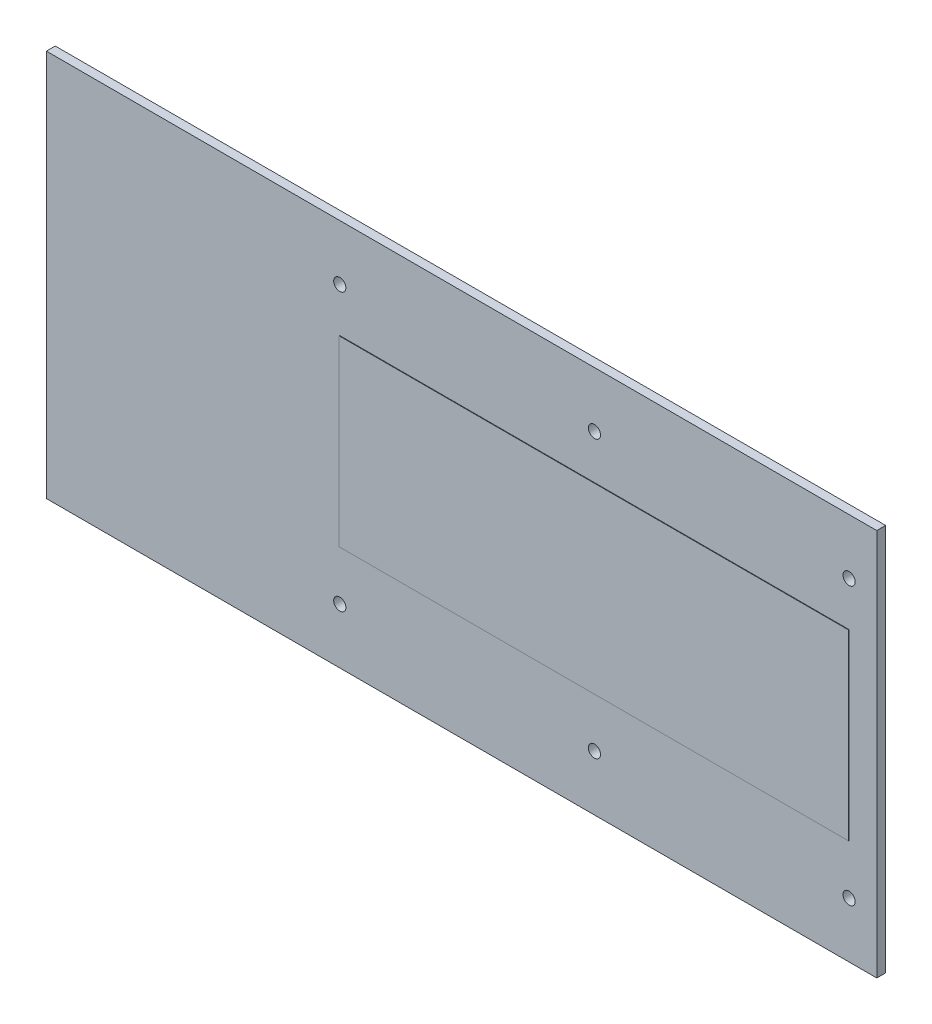
SolidWorks part; units mm, degrees
ref_plane "Front Plane" through (0, 0, 0) normal (0, 0, 1) x (1, 0, 0)
ref_plane "Top Plane" through (0, 0, 0) normal (0, 1, 0) x (1, 0, 0)
ref_plane "Right Plane" through (0, 0, 0) normal (1, 0, 0) x (0, 0, -1)
curve "ImportedCurve1"
curve "ImportedCurve2"
curve "ImportedCurve3"
curve "ImportedCurve4"
curve "ImportedCurve5"
curve "ImportedCurve6"
curve "ImportedCurve7"
curve "ImportedCurve8"
curve "ImportedCurve9"
curve "ImportedCurve10"
curve "ImportedCurve11"
curve "ImportedCurve12"
curve "ImportedCurve13"
curve "ImportedCurve14"
curve "ImportedCurve15"
curve "ImportedCurve16"
curve "ImportedCurve17"
curve "ImportedCurve18"
curve "ImportedCurve19"
curve "ImportedCurve20"
curve "ImportedCurve21"
curve "ImportedCurve22"
curve "ImportedCurve23"
curve "ImportedCurve24"
curve "ImportedCurve25"
curve "ImportedCurve26"
curve "ImportedCurve27"
curve "ImportedCurve28"
curve "ImportedCurve29"
curve "ImportedCurve30"
curve "ImportedCurve31"
curve "ImportedCurve32"
curve "ImportedCurve33"
curve "ImportedCurve34"
curve "ImportedCurve35"
curve "ImportedCurve36"
curve "ImportedCurve37"
curve "ImportedCurve38"
curve "ImportedCurve39"
curve "ImportedCurve40"
curve "ImportedCurve41"
curve "ImportedCurve42"
curve "ImportedCurve43"
curve "ImportedCurve44"
curve "ImportedCurve45"
curve "ImportedCurve46"
curve "ImportedCurve47"
curve "ImportedCurve48"
curve "ImportedCurve49"
curve "ImportedCurve50"
curve "ImportedCurve51"
curve "ImportedCurve52"
curve "ImportedCurve53"
curve "ImportedCurve54"
curve "ImportedCurve55"
curve "ImportedCurve56"
curve "ImportedCurve57"
curve "ImportedCurve58"
curve "ImportedCurve59"
curve "ImportedCurve60"
curve "ImportedCurve61"
curve "ImportedCurve62"
curve "ImportedCurve63"
curve "ImportedCurve64"
curve "ImportedCurve65"
curve "ImportedCurve66"
curve "ImportedCurve67"
curve "ImportedCurve68"
curve "ImportedCurve69"
curve "ImportedCurve70"
curve "ImportedCurve71"
curve "ImportedCurve72"
curve "ImportedCurve73"
curve "ImportedCurve74"
curve "ImportedCurve75"
curve "ImportedCurve76"
curve "ImportedCurve77"
curve "ImportedCurve78"
curve "ImportedCurve79"
curve "ImportedCurve80"
curve "ImportedCurve81"
curve "ImportedCurve82"
curve "ImportedCurve83"
curve "ImportedCurve84"
curve "ImportedCurve85"
curve "ImportedCurve86"
curve "ImportedCurve87"
curve "ImportedCurve88"
curve "ImportedCurve89"
curve "ImportedCurve90"
curve "ImportedCurve91"
curve "ImportedCurve92"
curve "ImportedCurve93"
curve "ImportedCurve94"
curve "ImportedCurve95"
curve "ImportedCurve96"
curve "ImportedCurve97"
curve "ImportedCurve98"
curve "ImportedCurve99"
curve "ImportedCurve100"
curve "ImportedCurve101"
curve "ImportedCurve102"
curve "ImportedCurve103"
curve "ImportedCurve104"
curve "ImportedCurve105"
curve "ImportedCurve106"
curve "ImportedCurve107"
curve "ImportedCurve108"
curve "ImportedCurve109"
curve "ImportedCurve110"
curve "ImportedCurve111"
curve "ImportedCurve112"
curve "ImportedCurve113"
curve "ImportedCurve114"
curve "ImportedCurve115"
curve "ImportedCurve116"
curve "ImportedCurve117"
curve "ImportedCurve118"
curve "ImportedCurve119"
curve "ImportedCurve120"
curve "ImportedCurve121"
curve "ImportedCurve122"
curve "ImportedCurve123"
curve "ImportedCurve124"
curve "ImportedCurve125"
curve "ImportedCurve126"
curve "ImportedCurve127"
curve "ImportedCurve128"
curve "ImportedCurve129"
curve "ImportedCurve130"
curve "ImportedCurve131"
curve "ImportedCurve132"
curve "ImportedCurve133"
curve "ImportedCurve134"
curve "ImportedCurve135"
curve "ImportedCurve136"
curve "ImportedCurve137"
curve "ImportedCurve138"
curve "ImportedCurve139"
curve "ImportedCurve140"
curve "ImportedCurve141"
curve "ImportedCurve142"
curve "ImportedCurve143"
curve "ImportedCurve144"
curve "ImportedCurve145"
curve "ImportedCurve146"
curve "ImportedCurve147"
curve "ImportedCurve148"
curve "ImportedCurve149"
curve "ImportedCurve150"
curve "ImportedCurve151"
curve "ImportedCurve152"
curve "ImportedCurve153"
curve "ImportedCurve154"
curve "ImportedCurve155"
curve "ImportedCurve156"
curve "ImportedCurve157"
curve "ImportedCurve158"
curve "ImportedCurve159"
curve "ImportedCurve160"
curve "ImportedCurve161"
curve "ImportedCurve162"
curve "ImportedCurve163"
curve "ImportedCurve164"
curve "ImportedCurve165"
curve "ImportedCurve166"
curve "ImportedCurve167"
curve "ImportedCurve168"
curve "ImportedCurve169"
curve "ImportedCurve170"
curve "ImportedCurve171"
curve "ImportedCurve172"
curve "ImportedCurve173"
curve "ImportedCurve174"
curve "ImportedCurve175"
curve "ImportedCurve176"
curve "ImportedCurve177"
curve "ImportedCurve178"
curve "ImportedCurve179"
curve "ImportedCurve180"
curve "ImportedCurve181"
curve "ImportedCurve182"
curve "ImportedCurve183"
curve "ImportedCurve184"
curve "ImportedCurve185"
curve "ImportedCurve186"
curve "ImportedCurve187"
curve "ImportedCurve188"
curve "ImportedCurve189"
curve "ImportedCurve190"
curve "ImportedCurve191"
curve "ImportedCurve192"
curve "ImportedCurve193"
curve "ImportedCurve194"
curve "ImportedCurve195"
curve "ImportedCurve196"
curve "ImportedCurve197"
curve "ImportedCurve198"
curve "ImportedCurve199"
curve "ImportedCurve200"
curve "ImportedCurve201"
curve "ImportedCurve202"
curve "ImportedCurve203"
curve "ImportedCurve204"
curve "ImportedCurve205"
curve "ImportedCurve206"
curve "ImportedCurve207"
curve "ImportedCurve208"
curve "ImportedCurve209"
curve "ImportedCurve210"
curve "ImportedCurve211"
curve "ImportedCurve212"
curve "ImportedCurve213"
curve "ImportedCurve214"
curve "ImportedCurve215"
curve "ImportedCurve216"
curve "ImportedCurve217"
curve "ImportedCurve218"
curve "ImportedCurve219"
curve "ImportedCurve220"
curve "ImportedCurve221"
curve "ImportedCurve222"
curve "ImportedCurve223"
curve "ImportedCurve224"
curve "ImportedCurve225"
curve "ImportedCurve226"
curve "ImportedCurve227"
curve "ImportedCurve228"
curve "ImportedCurve229"
curve "ImportedCurve230"
curve "ImportedCurve231"
curve "ImportedCurve232"
curve "ImportedCurve233"
curve "ImportedCurve234"
curve "ImportedCurve235"
curve "ImportedCurve236"
curve "ImportedCurve237"
curve "ImportedCurve238"
curve "ImportedCurve239"
curve "ImportedCurve240"
curve "ImportedCurve241"
curve "ImportedCurve242"
curve "ImportedCurve243"
curve "ImportedCurve244"
curve "ImportedCurve245"
curve "ImportedCurve246"
curve "ImportedCurve247"
curve "ImportedCurve248"
curve "ImportedCurve249"
curve "ImportedCurve250"
curve "ImportedCurve251"
curve "ImportedCurve252"
curve "ImportedCurve253"
curve "ImportedCurve254"
curve "ImportedCurve255"
curve "ImportedCurve256"
curve "ImportedCurve257"
curve "ImportedCurve258"
curve "ImportedCurve259"
curve "ImportedCurve260"
curve "ImportedCurve261"
curve "ImportedCurve262"
curve "ImportedCurve263"
curve "ImportedCurve264"
curve "ImportedCurve265"
curve "ImportedCurve266"
curve "ImportedCurve267"
curve "ImportedCurve268"
curve "ImportedCurve269"
curve "ImportedCurve270"
curve "ImportedCurve271"
curve "ImportedCurve272"
curve "ImportedCurve273"
curve "ImportedCurve274"
curve "ImportedCurve275"
curve "ImportedCurve276"
curve "ImportedCurve277"
curve "ImportedCurve278"
curve "ImportedCurve279"
curve "ImportedCurve280"
curve "ImportedCurve281"
curve "ImportedCurve282"
curve "ImportedCurve283"
curve "ImportedCurve284"
curve "ImportedCurve285"
curve "ImportedCurve286"
curve "ImportedCurve287"
curve "ImportedCurve288"
curve "ImportedCurve289"
curve "ImportedCurve290"
curve "ImportedCurve291"
curve "ImportedCurve292"
curve "ImportedCurve293"
curve "ImportedCurve294"
curve "ImportedCurve295"
curve "ImportedCurve296"
curve "ImportedCurve297"
curve "ImportedCurve298"
curve "ImportedCurve299"
curve "ImportedCurve300"
curve "ImportedCurve301"
curve "ImportedCurve302"
curve "ImportedCurve303"
curve "ImportedCurve304"
curve "ImportedCurve305"
curve "ImportedCurve306"
curve "ImportedCurve307"
curve "ImportedCurve308"
curve "ImportedCurve309"
curve "ImportedCurve310"
curve "ImportedCurve311"
curve "ImportedCurve312"
curve "ImportedCurve313"
curve "ImportedCurve314"
curve "ImportedCurve315"
curve "ImportedCurve316"
curve "ImportedCurve317"
curve "ImportedCurve318"
curve "ImportedCurve319"
curve "ImportedCurve320"
curve "ImportedCurve321"
curve "ImportedCurve322"
curve "ImportedCurve323"
curve "ImportedCurve324"
curve "ImportedCurve325"
curve "ImportedCurve326"
curve "ImportedCurve327"
curve "ImportedCurve328"
curve "ImportedCurve329"
curve "ImportedCurve330"
curve "ImportedCurve331"
curve "ImportedCurve332"
curve "ImportedCurve333"
curve "ImportedCurve334"
curve "ImportedCurve335"
curve "ImportedCurve336"
curve "ImportedCurve337"
curve "ImportedCurve338"
curve "ImportedCurve339"
curve "ImportedCurve340"
curve "ImportedCurve341"
curve "ImportedCurve342"
curve "ImportedCurve343"
curve "ImportedCurve344"
curve "ImportedCurve345"
curve "ImportedCurve346"
curve "ImportedCurve347"
curve "ImportedCurve348"
curve "ImportedCurve349"
curve "ImportedCurve350"
curve "ImportedCurve351"
curve "ImportedCurve352"
curve "ImportedCurve353"
curve "ImportedCurve354"
curve "ImportedCurve355"
curve "ImportedCurve356"
curve "ImportedCurve357"
curve "ImportedCurve358"
curve "ImportedCurve359"
curve "ImportedCurve360"
curve "ImportedCurve361"
curve "ImportedCurve362"
curve "ImportedCurve363"
curve "ImportedCurve364"
curve "ImportedCurve365"
curve "ImportedCurve366"
curve "ImportedCurve367"
curve "ImportedCurve368"
curve "ImportedCurve369"
curve "ImportedCurve370"
curve "ImportedCurve371"
curve "ImportedCurve372"
curve "ImportedCurve373"
curve "ImportedCurve374"
curve "ImportedCurve375"
curve "ImportedCurve376"
curve "ImportedCurve377"
curve "ImportedCurve378"
curve "ImportedCurve379"
curve "ImportedCurve380"
curve "ImportedCurve381"
curve "ImportedCurve382"
curve "ImportedCurve383"
curve "ImportedCurve384"
curve "ImportedCurve385"
curve "ImportedCurve386"
curve "ImportedCurve387"
curve "ImportedCurve388"
curve "ImportedCurve389"
curve "ImportedCurve390"
curve "ImportedCurve391"
curve "ImportedCurve392"
curve "ImportedCurve393"
curve "ImportedCurve394"
curve "ImportedCurve395"
curve "ImportedCurve396"
curve "ImportedCurve397"
curve "ImportedCurve398"
curve "ImportedCurve399"
curve "ImportedCurve400"
curve "ImportedCurve401"
curve "ImportedCurve402"
curve "ImportedCurve403"
curve "ImportedCurve404"
curve "ImportedCurve405"
curve "ImportedCurve406"
curve "ImportedCurve407"
curve "ImportedCurve408"
curve "ImportedCurve409"
curve "ImportedCurve410"
curve "ImportedCurve411"
curve "ImportedCurve412"
curve "ImportedCurve413"
curve "ImportedCurve414"
curve "ImportedCurve415"
curve "ImportedCurve416"
curve "ImportedCurve417"
curve "ImportedCurve418"
curve "ImportedCurve419"
curve "ImportedCurve420"
curve "ImportedCurve421"
curve "ImportedCurve422"
curve "ImportedCurve423"
curve "ImportedCurve424"
curve "ImportedCurve425"
curve "ImportedCurve426"
curve "ImportedCurve427"
curve "ImportedCurve428"
curve "ImportedCurve429"
curve "ImportedCurve430"
curve "ImportedCurve431"
curve "ImportedCurve432"
curve "ImportedCurve433"
curve "ImportedCurve434"
curve "ImportedCurve435"
curve "ImportedCurve436"
curve "ImportedCurve437"
curve "ImportedCurve438"
curve "ImportedCurve439"
curve "ImportedCurve440"
curve "ImportedCurve441"
curve "ImportedCurve442"
curve "ImportedCurve443"
curve "ImportedCurve444"
curve "ImportedCurve445"
curve "ImportedCurve446"
curve "ImportedCurve447"
curve "ImportedCurve448"
curve "ImportedCurve449"
curve "ImportedCurve450"
curve "ImportedCurve451"
curve "ImportedCurve452"
curve "ImportedCurve453"
curve "ImportedCurve454"
curve "ImportedCurve455"
curve "ImportedCurve456"
curve "ImportedCurve457"
curve "ImportedCurve458"
curve "ImportedCurve459"
curve "ImportedCurve460"
curve "ImportedCurve461"
curve "ImportedCurve462"
curve "ImportedCurve463"
curve "ImportedCurve464"
curve "ImportedCurve465"
curve "ImportedCurve466"
curve "ImportedCurve467"
curve "ImportedCurve468"
curve "ImportedCurve469"
curve "ImportedCurve470"
curve "ImportedCurve471"
curve "ImportedCurve472"
curve "ImportedCurve473"
curve "ImportedCurve474"
curve "ImportedCurve475"
curve "ImportedCurve476"
curve "ImportedCurve477"
curve "ImportedCurve478"
curve "ImportedCurve479"
curve "ImportedCurve480"
curve "ImportedCurve481"
curve "ImportedCurve482"
curve "ImportedCurve483"
curve "ImportedCurve484"
curve "ImportedCurve485"
curve "ImportedCurve486"
curve "ImportedCurve487"
curve "ImportedCurve488"
curve "ImportedCurve489"
curve "ImportedCurve490"
curve "ImportedCurve491"
curve "ImportedCurve492"
curve "ImportedCurve493"
curve "ImportedCurve494"
curve "ImportedCurve495"
curve "ImportedCurve496"
curve "ImportedCurve497"
curve "ImportedCurve498"
curve "ImportedCurve499"
curve "ImportedCurve500"
curve "ImportedCurve501"
curve "ImportedCurve502"
curve "ImportedCurve503"
curve "ImportedCurve504"
curve "ImportedCurve505"
curve "ImportedCurve506"
curve "ImportedCurve507"
curve "ImportedCurve508"
curve "ImportedCurve509"
curve "ImportedCurve510"
curve "ImportedCurve511"
curve "ImportedCurve512"
curve "ImportedCurve513"
curve "ImportedCurve514"
curve "ImportedCurve515"
curve "ImportedCurve516"
curve "ImportedCurve517"
curve "ImportedCurve518"
curve "ImportedCurve519"
curve "ImportedCurve520"
curve "ImportedCurve521"
curve "ImportedCurve522"
curve "ImportedCurve523"
curve "ImportedCurve524"
curve "ImportedCurve525"
curve "ImportedCurve526"
curve "ImportedCurve527"
curve "ImportedCurve528"
curve "ImportedCurve529"
curve "ImportedCurve530"
curve "ImportedCurve531"
curve "ImportedCurve532"
curve "ImportedCurve533"
curve "ImportedCurve534"
curve "ImportedCurve535"
curve "ImportedCurve536"
curve "ImportedCurve537"
curve "ImportedCurve538"
curve "ImportedCurve539"
curve "ImportedCurve540"
curve "ImportedCurve541"
curve "ImportedCurve542"
curve "ImportedCurve543"
curve "ImportedCurve544"
curve "ImportedCurve545"
curve "ImportedCurve546"
curve "ImportedCurve547"
curve "ImportedCurve548"
curve "ImportedCurve549"
curve "ImportedCurve550"
curve "ImportedCurve551"
curve "ImportedCurve552"
curve "ImportedCurve553"
curve "ImportedCurve554"
curve "ImportedCurve555"
curve "ImportedCurve556"
curve "ImportedCurve557"
curve "ImportedCurve558"
curve "ImportedCurve559"
curve "ImportedCurve560"
curve "ImportedCurve561"
curve "ImportedCurve562"
curve "ImportedCurve563"
curve "ImportedCurve564"
curve "ImportedCurve565"
curve "ImportedCurve566"
curve "ImportedCurve567"
curve "ImportedCurve568"
curve "ImportedCurve569"
curve "ImportedCurve570"
curve "ImportedCurve571"
curve "ImportedCurve572"
curve "ImportedCurve573"
curve "ImportedCurve574"
curve "ImportedCurve575"
curve "ImportedCurve576"
curve "ImportedCurve577"
curve "ImportedCurve578"
curve "ImportedCurve579"
curve "ImportedCurve580"
curve "ImportedCurve581"
curve "ImportedCurve582"
curve "ImportedCurve583"
curve "ImportedCurve584"
curve "ImportedCurve585"
curve "ImportedCurve586"
curve "ImportedCurve587"
curve "ImportedCurve588"
curve "ImportedCurve589"
curve "ImportedCurve590"
curve "ImportedCurve591"
curve "ImportedCurve592"
curve "ImportedCurve593"
curve "ImportedCurve594"
curve "ImportedCurve595"
curve "ImportedCurve596"
curve "ImportedCurve597"
curve "ImportedCurve598"
curve "ImportedCurve599"
curve "ImportedCurve600"
curve "ImportedCurve601"
curve "ImportedCurve602"
curve "ImportedCurve603"
curve "ImportedCurve604"
curve "ImportedCurve605"
curve "ImportedCurve606"
curve "ImportedCurve607"
curve "ImportedCurve608"
curve "ImportedCurve609"
curve "ImportedCurve610"
curve "ImportedCurve611"
curve "ImportedCurve612"
curve "ImportedCurve613"
curve "ImportedCurve614"
curve "ImportedCurve615"
curve "ImportedCurve616"
curve "ImportedCurve617"
curve "ImportedCurve618"
curve "ImportedCurve619"
curve "ImportedCurve620"
curve "ImportedCurve621"
curve "ImportedCurve622"
curve "ImportedCurve623"
curve "ImportedCurve624"
curve "ImportedCurve625"
curve "ImportedCurve626"
curve "ImportedCurve627"
curve "ImportedCurve628"
curve "ImportedCurve629"
curve "ImportedCurve630"
curve "ImportedCurve631"
curve "ImportedCurve632"
curve "ImportedCurve633"
curve "ImportedCurve634"
curve "ImportedCurve635"
curve "ImportedCurve636"
curve "ImportedCurve637"
curve "ImportedCurve638"
curve "ImportedCurve639"
curve "ImportedCurve640"
curve "ImportedCurve641"
curve "ImportedCurve642"
curve "ImportedCurve643"
curve "ImportedCurve644"
curve "ImportedCurve645"
curve "ImportedCurve646"
curve "ImportedCurve647"
curve "ImportedCurve648"
curve "ImportedCurve649"
curve "ImportedCurve650"
curve "ImportedCurve651"
curve "ImportedCurve652"
curve "ImportedCurve653"
curve "ImportedCurve654"
curve "ImportedCurve655"
curve "ImportedCurve656"
curve "ImportedCurve657"
curve "ImportedCurve658"
curve "ImportedCurve659"
curve "ImportedCurve660"
curve "ImportedCurve661"
curve "ImportedCurve662"
curve "ImportedCurve663"
sketch "Sketch1" plane through (0, 0, 0) normal (0, 0, 1) x (1, 0, 0)
  line L0 (48, 70) -> (150, 70) construction
  line L1 (150, 70) -> (150, 0) construction
  line L2 (0, 0) -> (0, 18.6) construction
  line L3 (48, 0) -> (46, 0) construction
  line L4 (150, 0) -> (48, 0) construction
  line L5 (46, 0) -> (0, 0) construction
  line L6 (0, 18.6) -> (0, 36) construction
  line L7 (0, 36) -> (0, 47) construction
  line L8 (0, 47) -> (0, 70) construction
  line L9 (0, 70) -> (48, 70) construction
  line L10 (48, 70) -> (150, 70)
  line L11 (150, 70) -> (150, 0)
  line L12 (0, 0) -> (0, 18.6)
  line L13 (48, 0) -> (46, 0)
  line L14 (150, 0) -> (48, 0)
  line L15 (46, 0) -> (0, 0)
  line L16 (0, 18.6) -> (0, 36)
  line L17 (0, 36) -> (0, 47)
  line L18 (0, 47) -> (0, 70)
  line L19 (0, 70) -> (48, 70)
  line L20 (9, 36) -> (0, 36) construction
  line L21 (0, 47) -> (9, 47) construction
  line L22 (9, 47) -> (9, 36) construction
  line L23 (46, 18.6) -> (46, 0) construction
  line L24 (46, 18.6) -> (0, 18.6) construction
  line L25 (48, 0) -> (48, 70) construction
  line L26 (145, 19) -> (145, 52) construction
  line L27 (53, 19) -> (145, 19) construction
  line L28 (53, 52) -> (53, 19) construction
  line L29 (145, 52) -> (53, 52) construction
  line L30 (9, 36) -> (0, 36) construction
  line L31 (0, 47) -> (9, 47) construction
  line L32 (9, 47) -> (9, 36) construction
  line L33 (46, 18.6) -> (46, 0) construction
  line L34 (46, 18.6) -> (0, 18.6) construction
  line L35 (48, 0) -> (48, 70) construction
  line L36 (145, 19) -> (145, 52)
  line L37 (53, 19) -> (145, 19)
  line L38 (53, 52) -> (53, 19)
  line L39 (145, 52) -> (53, 52)
  arc A0 (99, 11.1) -> (99, 8.9) centre (99, 10) ccw construction
  arc A1 (99, 8.9) -> (99, 11.1) centre (99, 10) ccw construction
  arc A2 (99, 61.1) -> (99, 58.9) centre (99, 60) ccw construction
  arc A3 (99, 58.9) -> (99, 61.1) centre (99, 60) ccw construction
  arc A4 (53, 61.1) -> (53, 58.9) centre (53, 60) ccw construction
  arc A5 (53, 58.9) -> (53, 61.1) centre (53, 60) ccw construction
  arc A6 (99, 11.1) -> (99, 8.9) centre (99, 10) ccw
  arc A7 (99, 8.9) -> (99, 11.1) centre (99, 10) ccw
  arc A8 (99, 61.1) -> (99, 58.9) centre (99, 60) ccw
  arc A9 (99, 58.9) -> (99, 61.1) centre (99, 60) ccw
  arc A10 (53, 61.1) -> (53, 58.9) centre (53, 60) ccw
  arc A11 (53, 58.9) -> (53, 61.1) centre (53, 60) ccw
  arc A12 (53, 11.1) -> (53, 8.9) centre (53, 10) ccw construction
  arc A13 (53, 8.9) -> (53, 11.1) centre (53, 10) ccw construction
  arc A14 (145, 11.1) -> (145, 8.9) centre (145, 10) ccw construction
  arc A15 (145, 8.9) -> (145, 11.1) centre (145, 10) ccw construction
  arc A16 (145, 61.1) -> (145, 58.9) centre (145, 60) ccw construction
  arc A17 (145, 58.9) -> (145, 61.1) centre (145, 60) ccw construction
  arc A18 (53, 11.1) -> (53, 8.9) centre (53, 10) ccw
  arc A19 (53, 8.9) -> (53, 11.1) centre (53, 10) ccw
  arc A20 (145, 11.1) -> (145, 8.9) centre (145, 10) ccw
  arc A21 (145, 8.9) -> (145, 11.1) centre (145, 10) ccw
  arc A22 (145, 61.1) -> (145, 58.9) centre (145, 60) ccw
  arc A23 (145, 58.9) -> (145, 61.1) centre (145, 60) ccw
extrude "Boss-Extrude1" add sketch "Sketch1" along normal blind 1.6
sketch "Sketch2" plane through (0, 0, 1.6) normal (0, 0, 1) x (1, 0, 0)
  line L1 (53, 52) -> (145, 52)
  line L2 (53, 52) -> (53, 19)
  line L3 (53, 19) -> (145, 19)
  line L4 (145, 52) -> (145, 19)
extrude "Boss-Extrude2" add sketch "Sketch2" along normal blind 0.1
ref_plane "Plane1" through (0, 35, 0) normal (0, -1, 0) x (-1, 0, 0)
